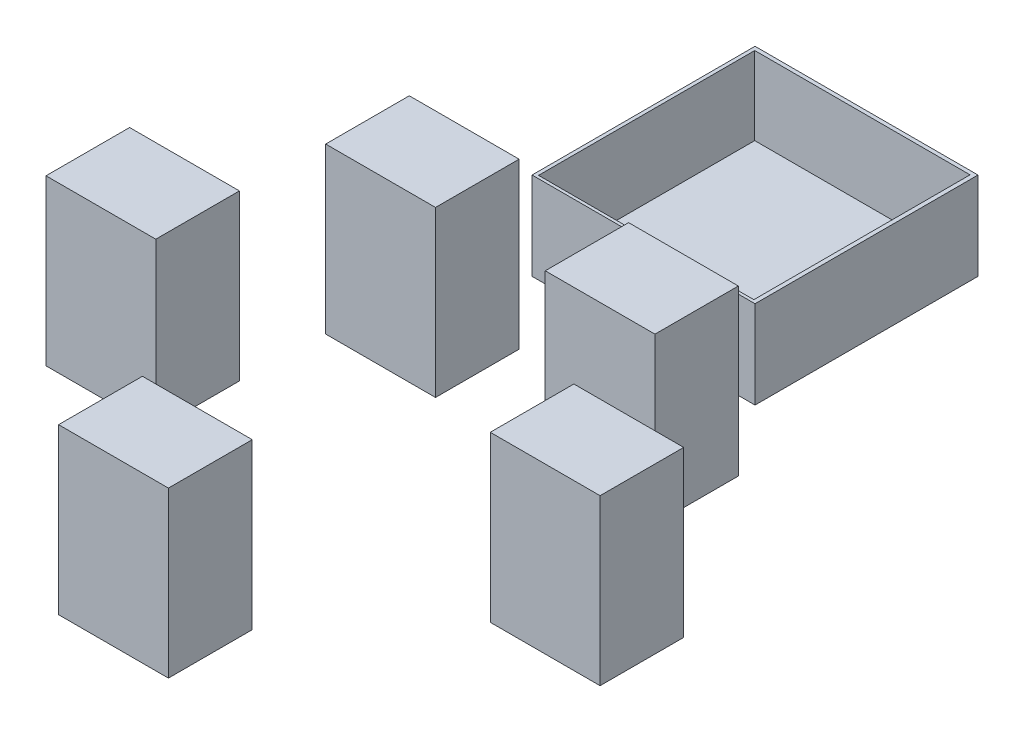
SolidWorks part; units mm, degrees
ref_plane "Front Plane" through (0, 0, 0) normal (0, 0, 1) x (1, 0, 0)
ref_plane "Top Plane" through (0, 0, 0) normal (0, 1, 0) x (1, 0, 0)
ref_plane "Right Plane" through (0, 0, 0) normal (1, 0, 0) x (0, 0, -1)
sketch "Sketch1" plane through (0, 0, 0) normal (0, 1, 0) x (1, 0, 0)
  line L1 (0, 0) -> (101.6, 0)
  line L2 (0, 0) -> (0, 101.6)
  line L3 (0, 101.6) -> (101.6, 101.6)
  line L4 (101.6, 0) -> (101.6, 101.6)
  dimension "D1" = 101.6
  dimension "D2" = 101.6
extrude "Boss-Extrude1" add sketch "Sketch1" along normal blind 39.9999
sketch "Sketch2" plane through (0, 39.9999, 0) normal (0, 1, 0) x (1, 0, 0)
  line L1 (1.6077, 99.8575) -> (99.7228, 99.8575)
  line L2 (1.6077, 99.8575) -> (1.6077, 1.3382)
  line L3 (1.6077, 1.3382) -> (99.7228, 1.3382)
  line L4 (99.7228, 99.8575) -> (99.7228, 1.3382)
extrude "Cut-Extrude1" cut sketch "Sketch2" against normal blind 35.56
sketch "Sketch3" plane through (0, 0, 0) normal (0, -1, 0) x (1, 0, 0)
  line L0 (101.6, -101.6) -> (50.8, -101.6) construction
  line L1 (101.6, -101.6) -> (0, -101.6) construction
  line L2 (50.8, -101.6) -> (50.8, 50.8) construction
  line L3 (50.8, 50.8) -> (25.8, 50.8) construction
  line L4 (50.8, 50.8) -> (75.8, 50.8) construction
  line L5 (25.8, 50.8) -> (25.8, 69.8) construction
  line L6 (75.8, 50.8) -> (75.8, 69.8) construction
  line L7 (50.8, 50.8) -> (50.8, 127) construction
  line L8 (75.8, 69.8) -> (125.7999, 69.8)
  line L9 (75.8, 69.8) -> (75.8, 31.8001)
  line L10 (75.8, 31.8001) -> (125.7999, 31.8001)
  line L11 (125.7999, 69.8) -> (125.7999, 31.8001)
  line L12 (25.8, 69.8) -> (-24.238, 69.8)
  line L13 (25.8, 69.8) -> (25.8, 31.7)
  line L14 (25.8, 31.7) -> (-24.238, 31.7)
  line L15 (-24.238, 69.8) -> (-24.238, 31.7)
  line L16 (50.8, 127) -> (50.8, 203.2) construction
  line L17 (50.8, 127) -> (-25.4, 127) construction
  line L18 (50.8, 127) -> (127, 127) construction
  line L19 (127, 127) -> (127, 146.05) construction
  line L20 (-25.4, 127) -> (-25.4, 146.05) construction
  line L21 (50.8, 203.2) -> (75.692, 203.2) construction
  line L23 (127, 146.05) -> (177.038, 146.05)
  line L24 (127, 146.05) -> (127, 107.95)
  line L25 (127, 107.95) -> (177.038, 107.95)
  line L26 (177.038, 146.05) -> (177.038, 107.95)
  line L27 (-25.4, 146.05) -> (-75.438, 146.05)
  line L28 (-25.4, 146.05) -> (-25.4, 107.95)
  line L29 (-25.4, 107.95) -> (-75.438, 107.95)
  line L30 (-75.438, 146.05) -> (-75.438, 107.95)
  line L35 (75.692, 203.2) -> (25.6473, 203.2)
  line L36 (75.692, 203.2) -> (75.692, 241.4005)
  line L37 (75.692, 241.4005) -> (25.6473, 241.4005)
  line L38 (25.6473, 203.2) -> (25.6473, 241.4005)
  dimension "D1" = 50.8
  dimension "D2" = 152.4
  dimension "D3" = 25
  dimension "D4" = 25
  dimension "D5" = 19
  dimension "D6" = 19
  dimension "D7" = 49.9999
  dimension "D8" = 37.9999
  dimension "D9" = 50.038
  dimension "D10" = 38.1
  dimension "D11" = 76.2
  dimension "D12" = 76.2
  dimension "D13" = 76.2
  dimension "D14" = 76.2
  dimension "D15" = 19.05
  dimension "D16" = 19.05
  dimension "D17" = 24.892
  dimension "D18" = 38.1
  dimension "D19" = 38.1
  dimension "D20" = 50.038
  dimension "D21" = 50.038
  dimension "D22" = 50.0447
  dimension "D23" = 38.2005
extrude "Boss-Extrude2" add sketch "Sketch3" against normal blind 75.0001 separate body
sketch "Sketch4" plane through (0, 0, 0) normal (0, -1, 0) x (1, 0, 0)
  line L1 (-74.296, 144.989) -> (-26.6227, 144.989)
  line L2 (-74.296, 144.989) -> (-74.296, 108.9879)
  line L3 (-74.296, 108.9879) -> (-26.6227, 108.9879)
  line L4 (-26.6227, 144.989) -> (-26.6227, 108.9879)
  line L5 (-22.6945, 68.1578) -> (24.6347, 68.1578)
  line L6 (-22.6945, 68.1578) -> (-22.6945, 32.6665)
  line L7 (-22.6945, 32.6665) -> (24.6347, 32.6665)
  line L8 (24.6347, 68.1578) -> (24.6347, 32.6665)
  line L9 (76.9968, 68.1578) -> (124.3821, 68.1578)
  line L10 (76.9968, 68.1578) -> (76.9968, 33.2532)
  line L11 (76.9968, 33.2532) -> (124.3821, 33.2532)
  line L12 (124.3821, 68.1578) -> (124.3821, 33.2532)
  line L13 (128.504, 144.989) -> (175.9629, 144.989)
  line L14 (128.504, 144.989) -> (128.504, 108.9879)
  line L15 (128.504, 108.9879) -> (175.9629, 108.9879)
  line L16 (175.9629, 144.989) -> (175.9629, 108.9879)
  line L17 (26.5641, 240.2403) -> (74.669, 240.2403)
  line L18 (26.5641, 240.2403) -> (26.5641, 204.2838)
  line L19 (26.5641, 204.2838) -> (74.669, 204.2838)
  line L20 (74.669, 240.2403) -> (74.669, 204.2838)
extrude "Cut-Extrude2" cut sketch "Sketch4" against normal blind 73.2221
sketch "Sketch5" plane through (0, 0, 31.7) normal (0, 0, -1) x (-1, 0, 0)
  line L0 (-0.781, 75.0001) -> (-0.781, 45.0281) construction
  line L1 (24.238, 75.0001) -> (-25.8, 75.0001) construction
  line L2 (-0.781, 45.0281) -> (-0.781, 54.9341) construction
  line L3 (-0.781, 54.9341) -> (-100.8, 54.9341) construction
  circle A0 centre (-0.781, 54.9341) radius 9.906
  circle A1 centre (-100.8, 54.9341) radius 9.9627
  dimension "D3" = 19.9254
  dimension "D1" = 29.972
  dimension "D2" = 9.906
extrude "Cut-Extrude3" cut sketch "Sketch5" against normal blind 9.7221
sketch "Sketch6" plane through (0, 0, 107.95) normal (0, 0, -1) x (-1, 0, 0)
  line L0 (-0.781, 54.9341) -> (50.419, 54.9341) construction
  line L1 (-0.781, 54.9341) -> (-152.019, 54.9341) construction
  circle A0 centre (-152.019, 54.9341) radius 9.906
  circle A1 centre (50.419, 54.9341) radius 9.906
  dimension "D1" = 19.812
  dimension "D2" = 19.812
extrude "Cut-Extrude4" cut sketch "Sketch6" against normal blind 9.7221
sketch "Sketch7" plane through (0, 0, 203.2) normal (0, 0, -1) x (-1, 0, 0)
  line L0 (-100.8, 54.9341) -> (-50.6696, 54.9341) construction
  circle A0 centre (-50.6696, 54.9341) radius 9.906
  dimension "D1" = 19.812
extrude "Cut-Extrude5" cut sketch "Sketch7" against normal blind 9.7221
